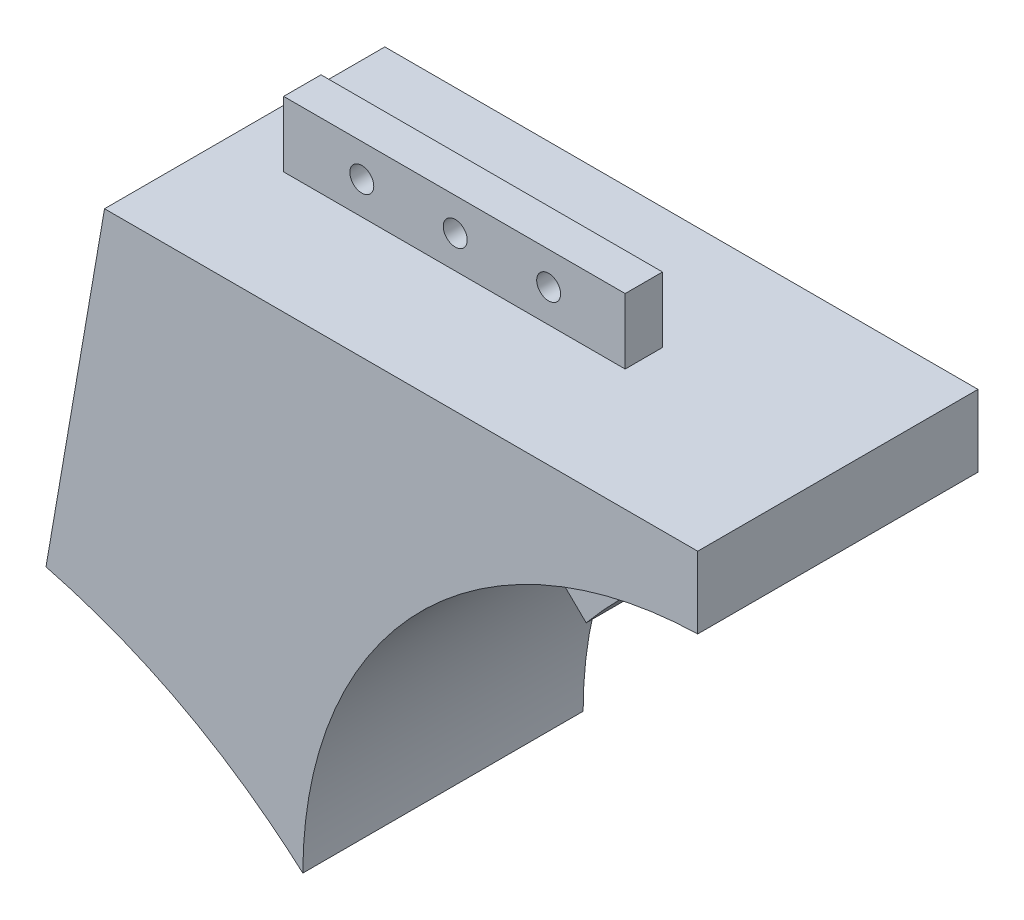
SolidWorks part; units mm, degrees
ref_plane "Front Plane" through (0, 0, 0) normal (0, 0, 1) x (1, 0, 0)
ref_plane "Top Plane" through (0, 0, 0) normal (0, 1, 0) x (1, 0, 0)
ref_plane "Right Plane" through (0, 0, 0) normal (1, 0, 0) x (0, 0, -1)
sketch "Sketch1" plane through (0, 0, 0) normal (0, 0, 1) x (1, 0, 0)
  line L0 (149.8559, -58.0677) -> (149.8559, 43.8748)
  line L1 (149.8559, 43.8748) -> (107.405, 43.8748)
  line L2 (107.405, 43.8748) -> (94.8747, -28.7787)
  line L3 (149.8559, 43.8748) -> (234.3838, 43.8748)
  line L4 (234.3838, 43.8748) -> (234.3838, 28.5235)
  line L5 (234.3838, 28.5235) -> (149.8559, 28.5235)
  line L6 (22.9369, 43.8748) -> (42.8134, 43.8748)
  line L7 (101.1845, -30.5679) -> (97.3203, -43.0485)
  line L8 (97.3203, -43.0485) -> (130.0729, -58.0677)
  line L9 (130.0729, -58.0677) -> (149.8559, -58.0677)
  line L10 (174.4912, 2.4364) -> (184.5094, -7.343)
  line L11 (119.7474, 43.8748) -> (192.854, 43.8748)
  line L12 (119.7474, 43.8748) -> (119.7474, 57.8748)
  line L13 (119.7474, 57.8748) -> (192.854, 57.8748)
  line L14 (192.854, 43.8748) -> (192.854, 57.8748)
  arc A0 (149.8559, -58.0677) -> (234.3838, 28.5235) centre (236.4723, -58.0677) cw
  circle A1 centre (109.0791, -40.7397) radius 2.5625
  circle A2 centre (128.1677, -49.4932) radius 2.5625
  circle A3 centre (136.4752, 50.8748) radius 2.5625
  circle A4 centre (185.5073, 3.7004) radius 2.563
  circle A5 centre (156.4752, 50.8748) radius 2.5625
  circle A6 centre (176.4752, 50.8748) radius 2.5625
  spline S0 degree 2 poles (94.8747, -28.7787) (125.8193, -36.7659) (149.8559, -58.0677) knots 0 0 0 1 1 1
  spline S1 degree 3 poles (45.9646, 43.8753) (45.1115, 43.8752) (43.0471, 43.875) (39.7711, 43.8742) (36.1357, 43.8733) (32.0958, 43.8731) (27.6523, 43.8739) (23.1651, 43.8749) (20.2937, 43.8752) (19.0374, 43.8753) knots 0 0 0 0 0.09512 0.23016 0.365129 0.500054 0.679977 0.859975 1 1 1 1 construction
  spline S2 degree 2 poles (184.5094, -7.343) (204.9306, 17.0782) (234.3838, 28.5235) knots 0 0 0 1 1 1
  dimension "D3" = 5.125
  dimension "D4" = 5.125
  dimension "D9" = 5.125
  dimension "D11" = 5.126
  dimension "D1" = 15.3513
  dimension "D2" = 15.3513
  dimension "D5" = 21
  dimension "D6" = 7
  dimension "D7" = 7
  dimension "D8" = 14
  dimension "D10" = 7
  dimension "D12" = 14
  dimension "D13" = 3
sketch "Sketch2" plane through (0, 0, 0) normal (0, 0, 1) x (1, 0, 0)
  line L0 (149.8559, -58.0677) -> (149.8559, 43.8748)
  line L1 (149.8559, 43.8748) -> (107.405, 43.8748)
  line L2 (107.405, 43.8748) -> (94.8747, -28.7787)
  line L3 (149.8559, 43.8748) -> (234.3838, 43.8748)
  line L4 (234.3838, 43.8748) -> (234.3838, 28.5235)
  line L5 (234.3838, 28.5235) -> (149.8559, 28.5235)
  line L6 (22.9369, 43.8748) -> (42.8134, 43.8748)
  line L7 (101.1845, -30.5679) -> (97.3203, -43.0485)
  line L8 (97.3203, -43.0485) -> (130.0729, -58.0677)
  line L9 (130.0729, -58.0677) -> (149.8559, -58.0677)
  line L10 (174.4912, 2.4364) -> (184.5094, -7.343)
  line L11 (119.7474, 43.8748) -> (192.854, 43.8748)
  line L12 (119.7474, 43.8748) -> (119.7474, 57.8748)
  line L13 (119.7474, 57.8748) -> (192.854, 57.8748)
  line L14 (192.854, 43.8748) -> (192.854, 57.8748)
  arc A0 (149.8559, -58.0677) -> (234.3838, 28.5235) centre (236.4723, -58.0677) cw
  circle A1 centre (109.0791, -40.7397) radius 2.5625
  circle A2 centre (128.1677, -49.4932) radius 2.5625
  circle A3 centre (136.4752, 50.8748) radius 2.5625
  circle A4 centre (185.5073, 3.7004) radius 2.563
  circle A5 centre (156.4752, 50.8748) radius 2.5625
  circle A6 centre (176.4752, 50.8748) radius 2.5625
  spline S0 degree 2 poles (94.8747, -28.7787) (125.8193, -36.7659) (149.8559, -58.0677) knots 0 0 0 1 1 1
  spline S2 degree 2 poles (184.5094, -7.343) (204.9306, 17.0782) (234.3838, 28.5235) knots 0 0 0 1 1 1
  dimension "D3" = 5.125
  dimension "D4" = 5.125
  dimension "D9" = 5.125
  dimension "D11" = 5.126
  dimension "D1" = 15.3513
  dimension "D2" = 15.3513
  dimension "D5" = 21
  dimension "D6" = 7
  dimension "D7" = 7
  dimension "D8" = 14
  dimension "D10" = 7
  dimension "D12" = 14
  dimension "D13" = 3
sketch "Sketch3" plane through (0, 0, 0) normal (0, 0, 1) x (1, 0, 0)
  line L0 (149.8559, -58.0677) -> (149.8559, 43.8748)
  line L1 (149.8559, 43.8748) -> (107.405, 43.8748)
  line L2 (107.405, 43.8748) -> (94.8747, -28.7787)
  line L3 (149.8559, 43.8748) -> (234.3838, 43.8748)
  line L4 (234.3838, 43.8748) -> (234.3838, 28.5235)
  line L5 (234.3838, 28.5235) -> (149.8559, 28.5235)
  line L6 (22.9369, 43.8748) -> (42.8134, 43.8748)
  line L7 (101.1845, -30.5679) -> (97.3203, -43.0485)
  line L8 (97.3203, -43.0485) -> (130.0729, -58.0677)
  line L9 (130.0729, -58.0677) -> (149.8559, -58.0677)
  line L10 (174.4912, 2.4364) -> (184.5094, -7.343)
  line L11 (119.7474, 43.8748) -> (192.854, 43.8748)
  line L12 (119.7474, 43.8748) -> (119.7474, 57.8748)
  line L13 (119.7474, 57.8748) -> (192.854, 57.8748)
  line L14 (192.854, 43.8748) -> (192.854, 57.8748)
  arc A0 (149.8559, -58.0677) -> (234.3838, 28.5235) centre (236.4723, -58.0677) cw
  circle A1 centre (109.0791, -40.7397) radius 2.5625
  circle A2 centre (128.1677, -49.4932) radius 2.5625
  circle A3 centre (136.4752, 50.8748) radius 2.5625
  circle A4 centre (185.5073, 3.7004) radius 2.563
  circle A5 centre (156.4752, 50.8748) radius 2.5625
  circle A6 centre (176.4752, 50.8748) radius 2.5625
  spline S0 degree 2 poles (94.8747, -28.7787) (125.8193, -36.7659) (149.8559, -58.0677) knots 0 0 0 1 1 1
  spline S2 degree 2 poles (184.5094, -7.343) (204.9306, 17.0782) (234.3838, 28.5235) knots 0 0 0 1 1 1
  dimension "D3" = 5.125
  dimension "D4" = 5.125
  dimension "D9" = 5.125
  dimension "D11" = 5.126
  dimension "D1" = 15.3513
  dimension "D2" = 15.3513
  dimension "D5" = 21
  dimension "D6" = 7
  dimension "D7" = 7
  dimension "D8" = 14
  dimension "D10" = 7
  dimension "D12" = 14
  dimension "D13" = 3
extrude "right_main" add sketch "Sketch1" along normal blind 30 contours L2 S0 L0 L1 | L5 L4 L3 L0 | L0 A0 L5
sketch "leftScrws" plane through (0, 0, 0) normal (0, 0, 1) x (1, 0, 0)
  line L0 (149.8559, -58.0677) -> (149.8559, 43.8748)
  line L1 (149.8559, 43.8748) -> (107.405, 43.8748)
  line L2 (107.405, 43.8748) -> (94.8747, -28.7787)
  line L3 (149.8559, 43.8748) -> (234.3838, 43.8748)
  line L4 (234.3838, 43.8748) -> (234.3838, 28.5235)
  line L5 (234.3838, 28.5235) -> (149.8559, 28.5235)
  line L6 (22.9369, 43.8748) -> (42.8134, 43.8748)
  line L7 (101.1845, -30.5679) -> (97.3203, -43.0485)
  line L8 (97.3203, -43.0485) -> (130.0729, -58.0677)
  line L9 (130.0729, -58.0677) -> (149.8559, -58.0677)
  line L10 (174.4912, 2.4364) -> (184.5094, -7.343)
  line L11 (119.7474, 43.8748) -> (192.854, 43.8748)
  line L12 (119.7474, 43.8748) -> (119.7474, 57.8748)
  line L13 (119.7474, 57.8748) -> (192.854, 57.8748)
  line L14 (192.854, 43.8748) -> (192.854, 57.8748)
  arc A0 (149.8559, -58.0677) -> (234.3838, 28.5235) centre (236.4723, -58.0677) cw
  circle A1 centre (109.0791, -40.7397) radius 2.5625
  circle A2 centre (128.1677, -49.4932) radius 2.5625
  circle A3 centre (136.4752, 50.8748) radius 2.5625
  circle A4 centre (185.5073, 3.7004) radius 2.563
  circle A5 centre (156.4752, 50.8748) radius 2.5625
  circle A6 centre (176.4752, 50.8748) radius 2.5625
  spline S0 degree 2 poles (94.8747, -28.7787) (125.8193, -36.7659) (149.8559, -58.0677) knots 0 0 0 1 1 1
  spline S2 degree 2 poles (184.5094, -7.343) (204.9306, 17.0782) (234.3838, 28.5235) knots 0 0 0 1 1 1
  dimension "D3" = 5.125
  dimension "D4" = 5.125
  dimension "D9" = 5.125
  dimension "D11" = 5.126
  dimension "D1" = 15.3513
  dimension "D2" = 15.3513
  dimension "D5" = 21
  dimension "D6" = 7
  dimension "D7" = 7
  dimension "D8" = 14
  dimension "D10" = 7
  dimension "D12" = 14
  dimension "D13" = 3
extrude "rightScrews" add sketch "Sketch2" along normal blind 4 contours L3 L14 L13 L12 L1 A6 A5 A3 | L10 S2 A0 A4 | S0 L7 L8 L9 A2 A1
extrude "left_main" add sketch "Sketch3" against normal blind 30 contours L5 L4 L3 L0 | L2 S0 L0 L1 | L0 A0 L5
extrude "Boss-Extrude4" add sketch "leftScrws" against normal blind 4 contours L3 L14 L13 L12 L1 A6 A5 A3 | S0 L7 L8 L9 A2 A1 | L10 S2 A0 A4
